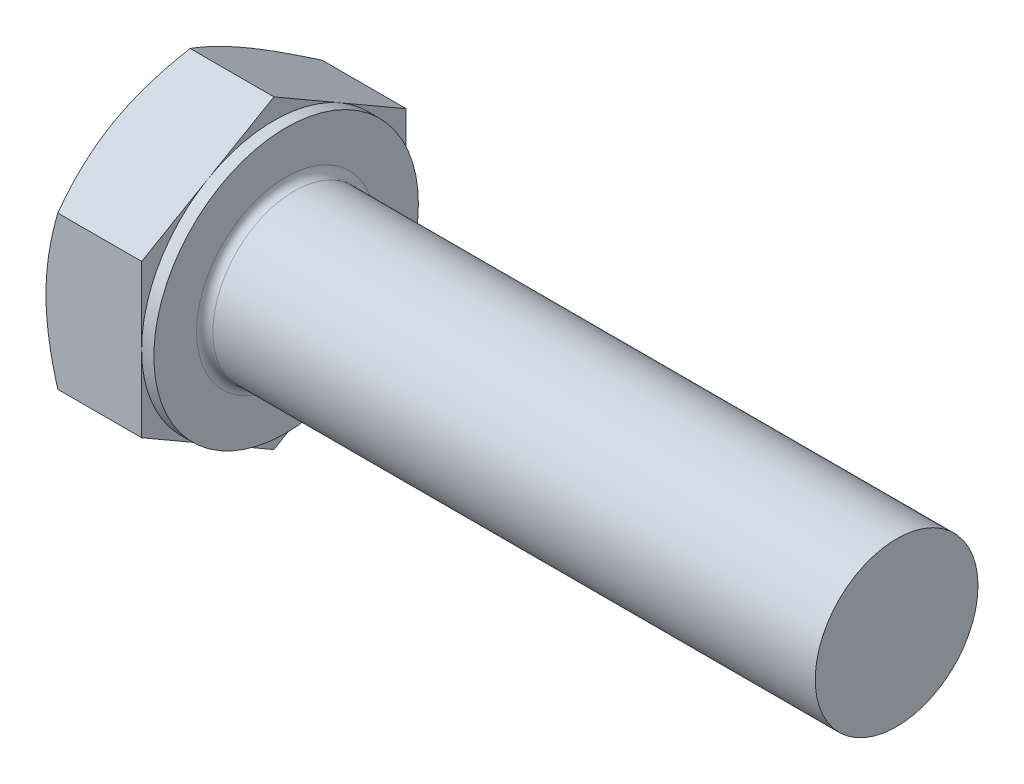
SolidWorks part; units mm, degrees
extrude "基体-拉伸" add sketch "草图1" along normal blind 5.3
sketch "草图1" plane through (0, 0, 0) normal (1, 0, 0) x (0, 0, -1)
  line L0 (6.5, 3.7528) -> (6.5, -3.7528)
  line L1 (-6.5, 3.7528) -> (-6.5, -3.7528)
  line L2 (6.5, -3.7528) -> (0, -7.5056)
  line L3 (0, -7.5056) -> (-6.5, -3.7528)
  line L4 (6.5, 3.7528) -> (0, 7.5056)
  line L5 (0, 7.5056) -> (-6.5, 3.7528)
  dimension "s" = 13
  dimension "D2" = 120
  dimension "D3" = 6.5
  dimension "D4" = 6.5
  dimension "D5" = 6.5
revolve "切除-旋转1" cut sketch "草图3" angle 360 about L6
sketch "草图3" plane through (0, 0, 0) normal (0, 0, 1) x (1, 0, 0)
  line L0 (0, 6.5) -> (3.4673, 12.5056)
  line L1 (0, 7.5056) -> (0, 3.7528) construction
  line L2 (3.4673, 12.5056) -> (3.4673, 17.5056)
  line L3 (3.4673, 17.5056) -> (-10, 17.5056)
  line L4 (-10, 17.5056) -> (-10, 6.5)
  line L5 (-10, 6.5) -> (0, 6.5)
  line L6 (0, 0) -> (99.06, 0) construction
  line L7 (5.3, 7.5056) -> (0, 7.5056) construction
  dimension "D1" = 6.5
  dimension "D2" = 5
  dimension "D3" = 10
  dimension "D4" = 5
  dimension "Head_ch_ang" = 30
revolve "凸台-旋转1" add sketch "草图2" angle 360 about L7
sketch "草图2" plane through (0, 0, 0) normal (0, 0, 1) x (1, 0, 0)
  line L0 (0, 3.7528) -> (0, -3.7528) construction
  line L1 (0, 0) -> (45.3, 0)
  line L2 (0, 0) -> (0, 4)
  line L3 (0, 4) -> (45.3, 4)
  line L4 (45.3, 0) -> (45.3, 2.9175)
  line L5 (5.3, 7.5056) -> (5.3, 3.7528) construction
  line L7 (0, 0) -> (96.52, 0) construction
  line L8 (45.3, -2.9175) -> (90.335, -4) construction
  line L9 (0, -4) -> (90.335, -4) construction
  line L10 (6.55, 15.24) -> (6.55, -1.27) construction
  line L11 (5.3, 15.24) -> (5.3, -1.27) construction
  line L12 (5.3, 3.7528) -> (5.3, -3.7528) construction
  line L14 (45.3, 4) -> (45.3, 2.9175)
  dimension "l" = 40
  dimension "m" = 8
  dimension "Minor_dia" = 5.835
  dimension "p" = 1.25
  dimension "h" = 40
cosmetic thread "螺旋线1" parameters "Thread_length"=38.75, "Thread_minor"=5.835
material "5.6级"
ref_plane "前视" through (0, 0, 0) normal (0, 0, 1) x (1, 0, 0)
ref_plane "上视" through (0, 0, 0) normal (0, 1, 0) x (1, 0, 0)
ref_plane "右视" through (0, 0, 0) normal (1, 0, 0) x (0, 0, -1)
sketch "草图5" plane through (0, 0, 0) normal (0, 0, 1) x (1, 0, 0)
  line L0 (5.3, 6.5) -> (1.8327, 12.5056)
  line L1 (5.3, 7.5056) -> (5.3, 3.7528) construction
  line L2 (1.8327, 12.5056) -> (1.8327, 17.5056)
  line L3 (1.8327, 17.5056) -> (11.8327, 17.5056)
  line L4 (11.8327, 17.5056) -> (11.8327, 6.5)
  line L5 (11.8327, 6.5) -> (5.3, 6.5)
  line L7 (5.3, 7.5056) -> (0.5806, 7.5056) construction
  line L8 (0, 0) -> (99.06, 0) construction
  line L9 (0, 0) -> (99.06, 0) construction
  dimension "D1" = 6.5
  dimension "D2" = 5
  dimension "D3" = 10
  dimension "D4" = 5
  dimension "Head_ch_ang" = 30
revolve "切除-旋转2" cut sketch "草图5" angle 360 about L8
sketch "草图4" plane through (0, 0, 0) normal (0, 0, 1) x (1, 0, 0)
  line L1 (5.3, 7.5056) -> (5.3, 3.7528) construction
  line L2 (5.3, 6.5) -> (4.7, 6.5)
  line L3 (5.3, 6.5) -> (5.3, 17.5056)
  line L4 (5.3, 17.5056) -> (4.7, 17.5056)
  line L5 (0, 0) -> (95.25, 0) construction
  line L6 (0, 0) -> (96.52, 0) construction
  line L7 (4.7, 6.5) -> (4.7, 17.5056)
  line L8 (4.7194, 7.5056) -> (0.5806, 7.5056) construction
  dimension "D2" = 10
  dimension "D1" = 13
revolve "切除-旋转3" cut sketch "草图4" angle 360 about L5
chamfer "倒角" distance 1 angle 45 1 edges at (45.3, 0, 4)
fillet "圆角" radius 0.4 1 edges at (5.3, 0, -4)
sketch "草图6" plane through (0, 0, 0) normal (0, 0, 1) x (1, 0, 0)
  line L0 (6.325, -2.9175) -> (5.7, -4)
  line L1 (6.325, -2.9175) -> (6.95, -4)
  line L2 (6.95, -4) -> (6.95, -5)
  line L3 (-3.175, 0) -> (5.1513, 0) construction
  line L5 (6.95, -5) -> (5.7, -5)
  line L6 (5.7, -5) -> (5.7, -4)
  arc A0 (5.7, -4) -> (5.3, -4.4) centre (5.7, -4.4) ccw construction
  dimension "Thread_minor" = 5.835
  dimension "Diameter" = 8
revolve "切除-旋转4" [suppressed] cut sketch "草图6" angle 360 about L3
pattern_linear "阵列(线性)1" [suppressed]
sketch "草图7" plane through (45.3, 0, 0) normal (1, 0, 0) x (0, 0, -1)
  circle A0 centre (0, 0) radius 6.0062
extrude "切除-拉伸1" cut sketch "草图7" against normal blind 10
equation "\"D3@草图1\" = \"s@草图1\" / 2"
equation "\"D4@草图1\" = \"D3@草图1\""
equation "\"D5@草图1\" = \"D4@草图1\""
equation "\"D1@草图3\" = \"s@草图1\" / 2"
equation "\"D1@草图5\" = \"s@草图1\" / 2"
equation "\"Head_ch_ang@草图5\" = \"Head_ch_ang@草图3\""
equation "\"D1@草图4\" = \"s@草图1\""
equation "\"Diameter@草图6\" = \"m@草图2\""
equation "\"Overcut@草图6\" = \"m@草图2\" * 1.25"
equation "\"Minor_dia@草图2\" = \"m@草图2\"-\"p@草图2\" * 1.732"
equation "\"Thread_minor@螺旋线1\" = \"Minor_dia@草图2\""
equation "\"Thread_minor@草图6\" = \"Minor_dia@草图2\""
equation "\"D1@倒角\" = \"p@草图2\"*0.8"
equation "\"Thread_length@螺旋线1\" = \"l@草图2\" - \"p@草图2\""
equation "\"Num_threads@阵列(线性)1\" = \"l@草图2\" / \"p@草图2\""
